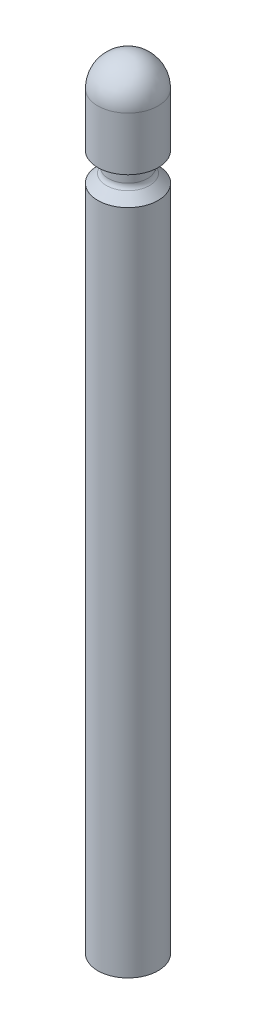
SolidWorks part; units mm, degrees
ref_plane "Front Plane" through (0, 0, 0) normal (0, 0, 1) x (1, 0, 0)
ref_plane "Top Plane" through (0, 0, 0) normal (0, 1, 0) x (1, 0, 0)
ref_plane "Right Plane" through (0, 0, 0) normal (1, 0, 0) x (0, 0, -1)
sketch "Sketch1" plane through (0, 0, 0) normal (0, 1, 0) x (1, 0, 0)
  circle A0 centre (0, 0) radius 3.3655
  dimension "D1" = 6.731
extrude "Boss-Extrude1" add sketch "Sketch1" along normal blind 86.9137
sketch "Sketch3" plane through (0, 86.9137, 0) normal (0, 1, 0) x (1, 0, 0)
  circle A0 centre (0, 0) radius 3.3655
ref_plane "Plane1" through (0, 0, 0) normal (0.2512, 0, 0.9679) x (0.9679, 0, -0.2512)
sketch "Sketch2" plane through (48.7909, 11.2673, -12.6643) normal (0.2512, 0, 0.9679) x (0.9679, 0, -0.2512)
  line L0 (-47.0422, 75.6464) -> (-53.7732, 75.6464) construction
  line L1 (-47.0422, 75.6464) -> (-53.7732, 75.6464) construction
  line L2 (-53.7732, 75.6464) -> (-53.7732, 66.3271) construction
  line L3 (-50.4077, 75.6464) -> (-50.4077, 50.6085) construction
  line L4 (-53.7732, 66.3271) -> (-53.3763, 66.3271)
  line L5 (-52.5826, 65.5334) -> (-52.5826, 64.6715)
  line L6 (-52.8151, 64.1103) -> (-53.7732, 63.1521)
  line L7 (-53.7732, 63.1521) -> (-53.7732, 66.3271)
  arc A0 (-52.5826, 64.6715) -> (-52.8151, 64.1103) centre (-53.3763, 64.6715) cw
  arc A1 (-53.3763, 66.3271) -> (-52.5826, 65.5334) centre (-53.3763, 65.5334) cw
  point P13 (-52.5826, 66.3271)
  dimension "D5" = 0.7937
  dimension "D1" = 9.3193
  dimension "D2" = 45
  dimension "D3" = 1.1906
  dimension "D4" = 3.175
revolve "Cut-Revolve2" cut sketch "Sketch2" angle 360 about L3
fillet "Fillet1" radius 3.3655 1 edges at (0, 86.9137, 3.3655)
